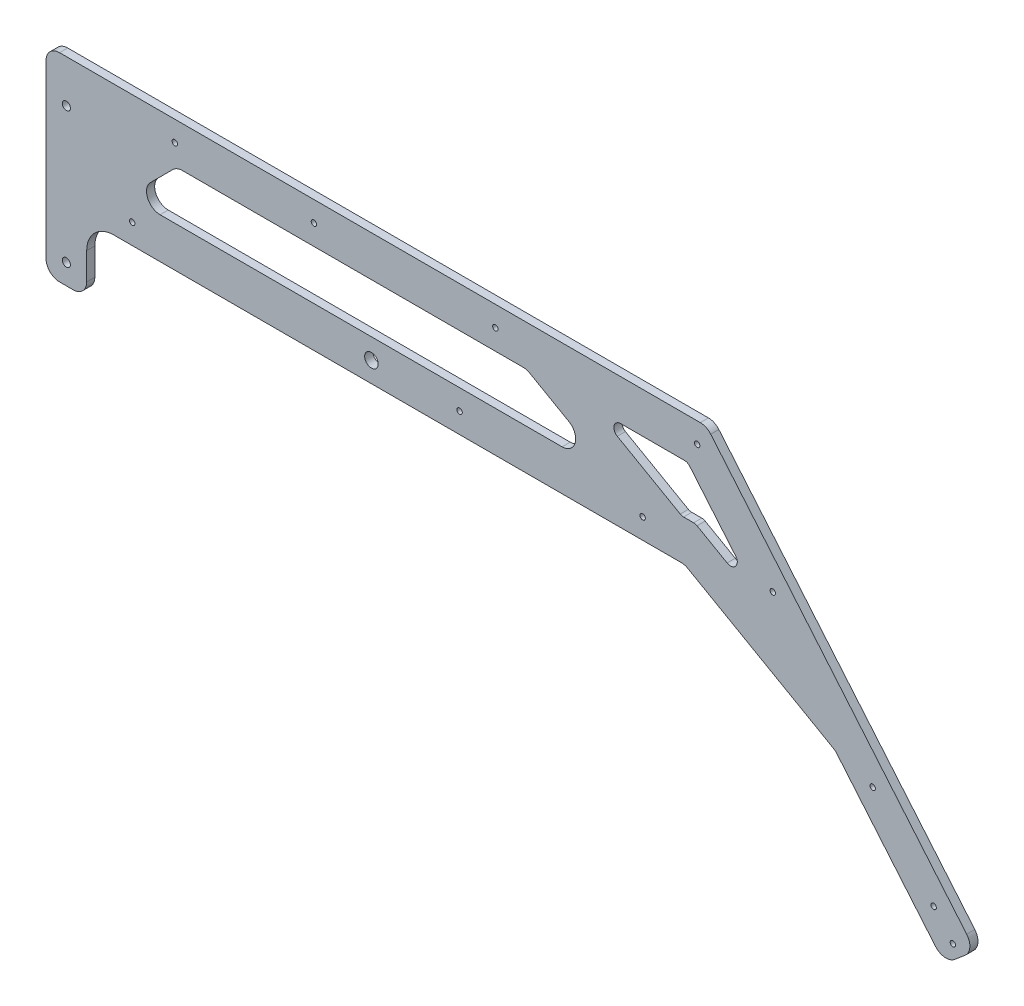
SolidWorks part; units mm, degrees
ref_plane "Front Plane" through (0, 0, 0) normal (0, 0, 1) x (1, 0, 0)
ref_plane "Top Plane" through (0, 0, 0) normal (0, 1, 0) x (1, 0, 0)
ref_plane "Right Plane" through (0, 0, 0) normal (1, 0, 0) x (0, 0, -1)
sketch "Sketch1" plane through (0, 0, 0) normal (0, 0, 1) x (1, 0, 0)
  line L0 (0, 0) -> (0, 146.44)
  line L1 (0, 146.44) -> (487.2246, 146.44)
  line L2 (487.2246, 146.44) -> (701.4944, -108.9168)
  line L3 (701.4944, -108.9168) -> (678.5131, -128.2004)
  line L4 (678.5131, -128.2004) -> (582.0949, -13.2938)
  line L5 (582.0949, -13.2938) -> (354.44, 116.44)
  line L6 (354.44, 116.44) -> (96.44, 116.44)
  line L7 (96.44, 116.44) -> (30, 50)
  line L8 (30, 50) -> (30, 0)
  line L9 (30, 0) -> (0, 0)
  line L10 (15, 0) -> (15, 131.44) construction
  line L11 (15, 131.44) -> (480.23, 131.44) construction
  line L12 (480.23, 131.44) -> (690.0037, -118.5586) construction
  line L13 (30, 50) -> (471.028, 50)
  line L14 (60, 80) -> (418.3844, 80)
  line L15 (15, 65) -> (444.7062, 65) construction
  line L16 (685.4247, -89.7657) -> (662.4434, -109.0493)
  circle A0 centre (654.6504, -76.4262) radius 2
  circle A1 centre (668.7917, -93.2791) radius 2
  circle A2 centre (15, 115) radius 3
  circle A3 centre (15, 15) radius 3
  circle A4 centre (240.0037, 65) radius 5
  dimension "D17" = 4
  dimension "D20" = 6
  dimension "D21" = 6
  dimension "D10" = 10
  dimension "D1" = 30
  dimension "D2" = 30
  dimension "D3" = 135
  dimension "D4" = 130
  dimension "D5" = 15
  dimension "D6" = 30
  dimension "D7" = 465.23
  dimension "D8" = 326.35
  dimension "D9" = 15
  dimension "D11" = 150
  dimension "D12" = 258
  dimension "D13" = 30
  dimension "D14" = 66.44
  dimension "D15" = 15
  dimension "D16" = 22
  dimension "D18" = 33
  dimension "D19" = 8
  dimension "D22" = 100
  dimension "D23" = 50
  dimension "D24" = 450
extrude "Boss-Extrude1" add sketch "Sketch1" along normal blind 6 contours L16 L2 L1 L0 L9 L8 L7 L6 L5 L4 A3 A2 A1 A0 | L14 L7 L13 L5 A4
fillet "Fillet1" radius 20 1 edges at (30, 50, 3)
fillet "Fillet2" radius 10 12 edges at (685.4247, -89.7657, 3) (662.4434, -109.0493, 3) (582.0949, -13.2938, 3) (471.028, 50, 3) (487.2246, 146.44, 3) (30, 0, 3) (0, 0, 3) (0, 146.44, 3) (96.44, 116.44, 3) (354.44, 116.44, 3) (418.3844, 80, 3) (60, 80, 3)
sketch "Sketch2" plane through (0, 0, 6) normal (0, 0, 1) x (1, 0, 0)
  line L0 (404.933, 116.44) -> (473.2354, 116.44)
  line L1 (473.2354, 116.44) -> (526.5711, 52.877)
  line L2 (526.5711, 52.877) -> (478.976, 80)
  line L3 (478.976, 80) -> (468.8774, 80)
  line L5 (490.222, 142.8679) -> (678.9968, -82.1052) construction
  line L6 (580.5377, -12.4064) -> (473.3298, 48.6883) construction
  line L7 (10, 146.44) -> (482.5615, 146.44) construction
  line L8 (50, 50) -> (468.3786, 50) construction
  line L9 (404.933, 116.44) -> (468.8774, 80)
  line L10 (385.5905, 98.6883) -> (356.7418, 115.1283) construction
  dimension "D1" = 30
  dimension "D2" = 30
  dimension "D3" = 30
  dimension "D4" = 30
  dimension "D5" = 25
extrude "Cut-Extrude1" cut sketch "Sketch2" against normal through all
fillet "Fillet3" radius 5 5 edges at (478.976, 80, 3) (468.8774, 80, 3) (526.5711, 52.877, 3) (473.2354, 116.44, 3) (404.933, 116.44, 3)
sketch "Sketch3" plane through (0, 0, 6) normal (0, 0, 1) x (1, 0, 0)
  circle A0 centre (609.6553, -22.803) radius 2 construction
  circle A1 centre (440.0037, 65) radius 2 construction
  circle A2 centre (535.9798, 65) radius 2 construction
  circle A3 centre (480.23, 131.44) radius 2 construction
  circle A4 centre (305.0037, 65) radius 2 construction
  circle A5 centre (331.3958, 131.44) radius 2 construction
  circle A6 centre (197.5615, 131.44) radius 2 construction
  circle A7 centre (609.6553, -22.803) radius 2
  circle A8 centre (440.0037, 65) radius 2
  circle A9 centre (535.9798, 65) radius 2
  circle A10 centre (480.23, 131.44) radius 2
  circle A11 centre (305.0037, 65) radius 2
  circle A12 centre (331.3958, 131.44) radius 2
  circle A13 centre (197.5615, 131.44) radius 2
extrude "Cut-Extrude2" cut sketch "Sketch3" against normal through all
sketch "Sketch9" plane through (0, 0, 6) normal (0, 0, 1) x (1, 0, 0)
  line L0 (10, 146.44) -> (482.5615, 146.44) construction
  line L1 (50, 50) -> (468.3786, 50) construction
  circle A0 centre (95, 131.44) radius 2
  circle A1 centre (63.56, 65) radius 2
  circle A2 centre (15, 115) radius 3 construction
  dimension "D1" = 4
  dimension "D4" = 80
  dimension "D2" = 15
  dimension "D3" = 15
  dimension "D5" = 31.44
extrude "Cut-Extrude4" cut sketch "Sketch9" against normal through all
